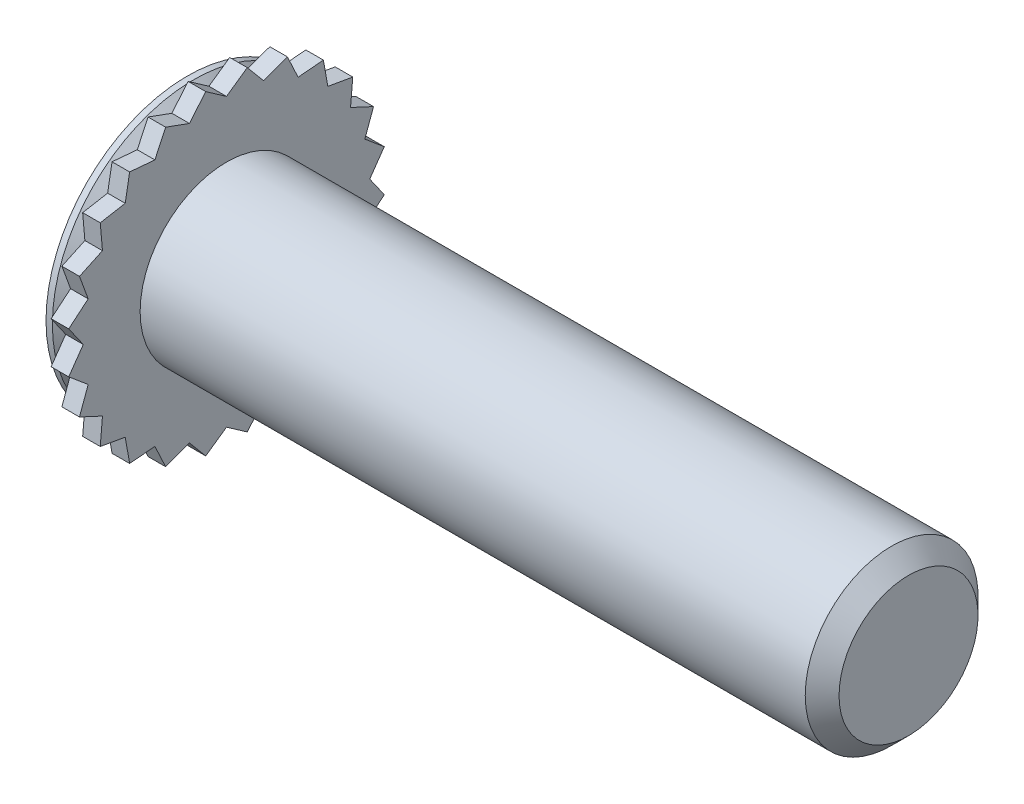
SolidWorks part; units mm, degrees
revolve "BaseBody" add sketch "BodySke" angle 360 about L6
sketch "BodySke" plane through (0, 0, 0) normal (0, 0, 1) x (1, 0, 0)
  line L0 (0, 2.2225) -> (0, 3.9497)
  line L1 (1.0922, 4.445) -> (0.6007, 4.445)
  line L2 (0.6007, 4.445) -> (0.6007, 3.636)
  line L3 (1.0922, 2.413) -> (19.6698, 2.413)
  line L4 (20.1422, 1.9406) -> (20.1422, 0)
  line L5 (20.1422, 0) -> (0.5461, 0)
  line L6 (0, 0) -> (50.554, 0) construction
  line L7 (1.0922, 4.445) -> (1.0922, 2.413)
  line L8 (20.1422, 1.9406) -> (19.6698, 2.413)
  line L9 (0.6007, 3.636) -> (0.4915, 3.636)
  line L10 (0.4915, 3.636) -> (0.1778, 3.9497)
  line L11 (1.8847, 19.05) -> (1.8847, -3.175) construction
  line L12 (0.1778, 3.9497) -> (0, 3.9497)
  line L13 (0, 2.2225) -> (0.5461, 1.6764)
  line L14 (0.5461, 1.6764) -> (0.5461, 0)
  dimension "Body_ch_ang" = 45
  dimension "Advance" = 0.7925
  dimension "Minor_dia" = 3.8811
  dimension "Diameter" = 4.826
  dimension "Length" = 19.05
  dimension "A_dim" = 1.0922
  dimension "Clinch_ht" = 0.4915
  dimension "E_dia" = 8.89
  dimension "C_dia" = 7.8994
  dimension "C_len" = 0.1778
  dimension "Skirt_ht" = 0.4915
  dimension "D1" = 45
  dimension "Face_clr_dep" = 0.5461
  dimension "Face_clr_dia" = 4.445
  dimension "Face_clr_ang" = 45
cosmetic thread "ThreadCosmetic" [suppressed] parameters "Thread_length"=17.4752, "Thread_minor"=3.8811
ref_plane "Plane1" through (0, 0, 0) normal (0, 0, 1) x (1, 0, 0)
ref_plane "Plane2" through (0, 0, 0) normal (0, 1, 0) x (1, 0, 0)
ref_plane "Plane3" through (0, 0, 0) normal (1, 0, 0) x (0, 0, -1)
sketch "ThdSchSke" plane through (0, 0, 0) normal (0, 0, 1) x (1, 0, 0)
  line L0 (2.667, -1.9406) -> (2.3362, -2.413)
  line L1 (2.667, -1.9406) -> (2.9978, -2.413)
  line L2 (2.9978, -2.413) -> (2.9978, -3.0162)
  line L3 (-3.175, 0) -> (5.1513, 0) construction
  line L5 (2.9978, -3.0162) -> (2.3362, -3.0162)
  line L6 (2.3362, -3.0162) -> (2.3362, -2.413)
  line L8 (1.0922, -2.413) -> (1.0922, 2.413) construction
  dimension "Diameter" = 4.826
  dimension "SideAngle" = 55
  dimension "VeeAngle" = 70
  dimension "Thread_minor" = 3.8811
  dimension "Overcut" = 6.0325
  dimension "Start" = 1.5748
revolve "ThreadSchematic" [suppressed] cut sketch "ThdSchSke" angle 360 about L3
pattern_linear "ThdSchPat" [suppressed]
sketch "CliRinCutSke" plane through (1.0922, 0, 0) normal (1, 0, 0) x (0, 0, -1)
  line L0 (0, 0) -> (0, 4.8256) construction
  line L1 (0.5802, 4.407) -> (0, 4.0005)
  line L2 (0, 4.0005) -> (-0.5802, 4.407)
  arc A0 (0.5802, 4.407) -> (-0.5802, 4.407) centre (0, 0) ccw
  circle A1 centre (0, 0) radius 4.445 construction
  circle A2 centre (0, 0) radius 4.0005 construction
  dimension "Angle" = 15
extrude "ClinchCut" cut sketch "CliRinCutSke" against normal blind 0.4915
pattern_circular "ClinchCutPat" count 24 every 15 about axis through (0, 0, 0) along (1, 0, 0) of "ClinchCut"
equation "' \"Length@BodySke\" = 0.75"
equation "' \"A_dim@BodySke\" = 0.043"
equation "' \"E_dia@BodySke\" = 0.35"
equation "' \"C_dia@BodySke\" = 0.311"
equation "' \"Diameter@BodySke\" = 0.19"
equation "' \"Minor_dia@BodySke\" = 0.1528"
equation "' \"Advance@BodySke\" = 0.0312"
equation "\"Face_clr_dia@BodySke\" = \"E_dia@BodySke\" / 2"
equation "\"Face_clr_dep@BodySke\" = \"A_dim@BodySke\" / 2"
equation "\"Start@ThdSchSke\" = 0.062"
equation "\"Skirt_ht@BodySke\" = \"A_dim@BodySke\" * 0.45"
equation "\"Clinch_ht@BodySke\" = \"A_dim@BodySke\" * 0.45"
equation "\"Depth@ClinchCut\" = \"A_dim@BodySke\" * 0.45"
equation "\"Count@ClinchCutPat\" = 24"
equation "\"Angle@ClinchCutPat\" = 360 / \"Count@ClinchCutPat\""
equation "\"Angle@CliRinCutSke\" = 360 / \"Count@ClinchCutPat\""
equation "\"Clinch_minor@CliRinCutSke\" =  \"C_dia@BodySke\" "
equation "\"Clinch_minor@CliRinCutSke\" =  \"E_dia@BodySke\" * 0.9"
equation "\"Thread_length@ThreadCosmetic\" = \"Length@BodySke\" - \"Start@ThdSchSke\""
equation "\"Thread_minor@ThreadCosmetic\" = \"Minor_dia@BodySke\""
equation "\"Thread_minor@ThdSchSke\" = \"Minor_dia@BodySke\""
equation "\"Diameter@ThdSchSke\" = \"Diameter@BodySke\""
equation "\"Overcut@ThdSchSke\" = \"Diameter@BodySke\" * 1.25"
equation "\"Num_threads@ThdSchPat\" = int( \"Thread_length@ThreadCosmetic\" / \"Advance@BodySke\" + 0.999 )  + 1"
equation "\"Advance@ThdSchPat\" = \"Thread_length@ThreadCosmetic\" /  (\"Num_threads@ThdSchPat\" - 1) 'relax it"
equation "\"Num_threads@ThdSchPat\" = \"Num_threads@ThdSchPat\" - sgn( \"Num_threads@ThdSchPat\" - 1) '---chamfered tips only---"
